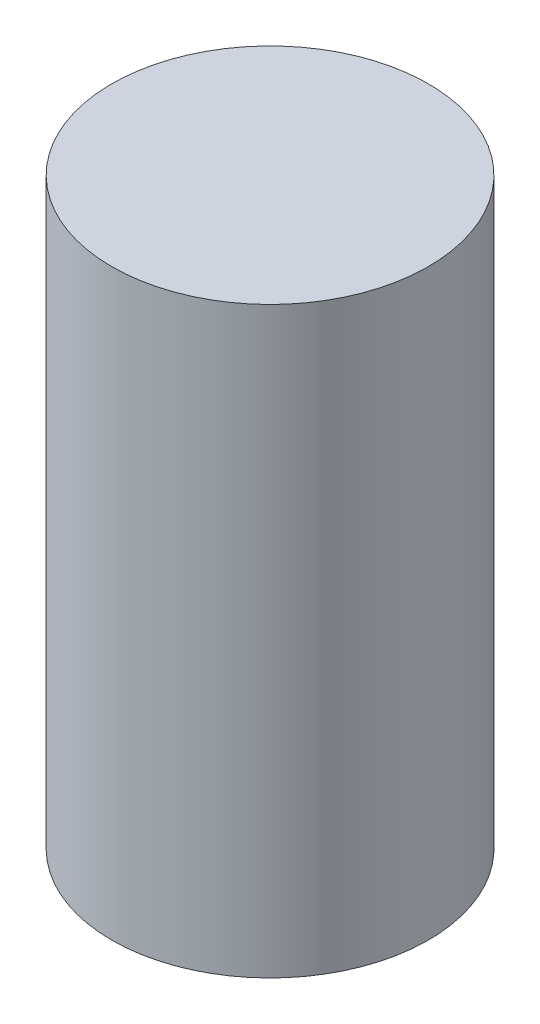
SolidWorks part; units mm, degrees
ref_plane "前视" through (0, 0, 0) normal (0, 0, 1) x (1, 0, 0)
ref_plane "上视" through (0, 0, 0) normal (0, 1, 0) x (1, 0, 0)
ref_plane "右视" through (0, 0, 0) normal (1, 0, 0) x (0, 0, -1)
sketch "草图1" plane through (0, 0, 0) normal (0, 1, 0) x (1, 0, 0)
  circle A0 centre (0, 0) radius 38
extrude "拉伸1" add sketch "草图1" along normal blind 140
shell "抽壳1" thickness 3
